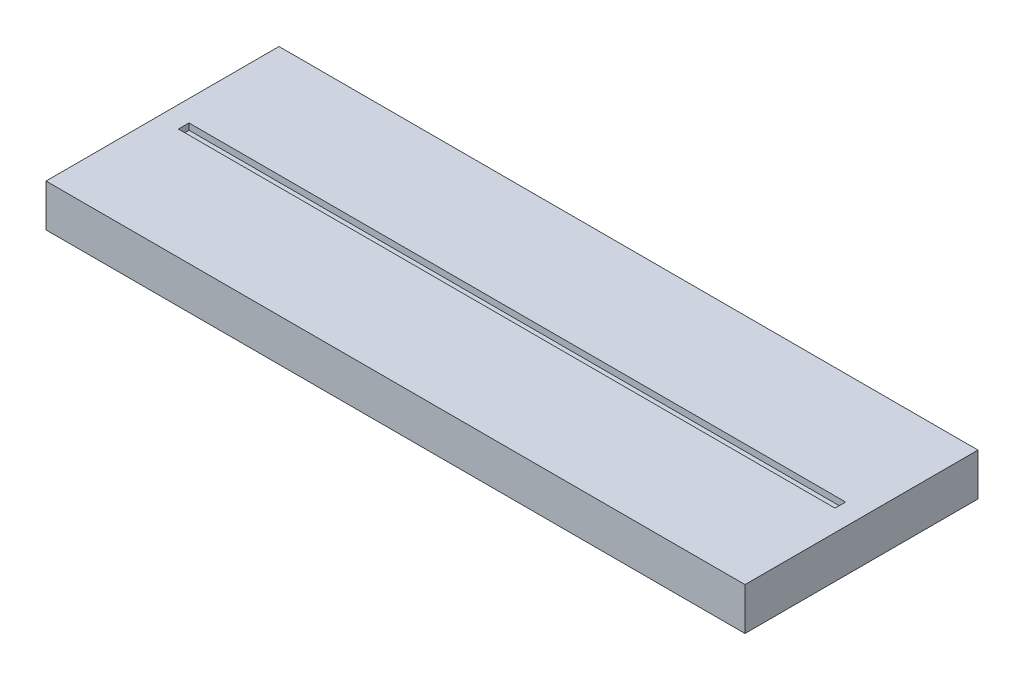
SolidWorks part; units mm, degrees
ref_plane "Front Plane" through (0, 0, 0) normal (0, 0, 1) x (1, 0, 0)
ref_plane "Top Plane" through (0, 0, 0) normal (0, 1, 0) x (1, 0, 0)
ref_plane "Right Plane" through (0, 0, 0) normal (1, 0, 0) x (0, 0, -1)
other "Configuration Table"
sketch "Sketch1" plane through (0, 0, 0) normal (0, 1, 0) x (1, 0, 0)
  line L1 (-82.5, -27.5) -> (82.5, -27.5)
  line L2 (-82.5, -27.5) -> (-82.5, 27.5)
  line L3 (-82.5, 27.5) -> (82.5, 27.5)
  line L4 (82.5, -27.5) -> (82.5, 27.5)
  line L5 (-82.5, -27.5) -> (82.5, 27.5) construction
  line L6 (-82.5, 27.5) -> (82.5, -27.5) construction
  point P6 (0, 0)
  dimension "D1" = 165
  dimension "D2" = 55
extrude "Body" add sketch "Sketch1" along normal blind 10
sketch "Sketch2" plane through (0, 0, 0) normal (0, 1, 0) x (1, 0, 0)
  line L0 (-77.5, -1.25) -> (77.5, -1.25)
  line L1 (77.5, -1.25) -> (77.5, 1.25)
  line L2 (77.5, 1.25) -> (-77.5, 1.25)
  line L3 (-77.5, 1.25) -> (-77.5, -1.25)
extrude "Centre_Channel" cut sketch "Sketch2" against normal blind 1.5 from offset 10
equation "\"Jar_OD\"= 90  'ASSUMED - Part G fallback - jar outer diameter"
equation "\"Jar_H\"= 120  'ASSUMED - Part G fallback - jar height"
equation "\"Pump_L\"= 45  'ASSUMED - Part G fallback"
equation "\"Pump_W\"= 24  'ASSUMED - Part G fallback"
equation "\"Pump_H\"= 33  'ASSUMED - Part G fallback"
equation "\"Pump_Outlet_OD\"= 7.5  'ASSUMED - Part G fallback"
equation "\"Tube_OD\"= 8  'ASSUMED - Part G fallback"
equation "\"Tube_ID\"= 6  'ASSUMED - Part G fallback"
equation "\"TDS_Body_Dia\"= 12  'ASSUMED - Part G fallback"
equation "\"TDS_Wet_Len\"= 45  'ASSUMED - Part G fallback - length in water"
equation "\"DS_Tube_Dia\"= 6  'ASSUMED - Part G fallback"
equation "\"DS_Tube_Len\"= 50  'ASSUMED - Part G fallback"
equation "\"ORP_Body_Dia\"= 12  'ASSUMED - Part G fallback"
equation "\"ORP_Body_Len\"= 150  'ASSUMED - Part G fallback"
equation "\"ORP_Cap_Dia\"= 16  'ASSUMED - Part G fallback"
equation "\"Turb_W\"= 33  'ASSUMED - Part G fallback - head width"
equation "\"Turb_D\"= 28  'ASSUMED - Part G fallback - head depth"
equation "\"Turb_H\"= 30  'ASSUMED - Part G fallback - head height"
equation "\"Turb_Slot_W\"= 10  'ASSUMED - Part G fallback - slot width"
equation "\"Flow_L\"= 62  'ASSUMED - Part G fallback YF-S201"
equation "\"Flow_W\"= 36  'ASSUMED - Part G fallback"
equation "\"Flow_H\"= 35  'ASSUMED - Part G fallback"
equation "\"Thread_G12_OD\"= 20.955  'ASSUMED - Part G fallback thread G1/2 (major diameter)"
equation "\"Valve_L\"= 75  'ASSUMED - Part G fallback"
equation "\"Valve_W\"= 45  'ASSUMED - Part G fallback"
equation "\"Valve_H\"= 60  'ASSUMED - Part G fallback"
equation "\"Tee_L\"= 40  'ASSUMED - Part G fallback - overall length"
equation "\"Tee_Branch_L\"= 25  'ASSUMED - Part G fallback"
equation "\"Tee_OD\"= 12  'ASSUMED - Part G fallback"
equation "\"LED_Board_L\"= 20  'ASSUMED - Part G fallback"
equation "\"LED_Board_W\"= 20  'ASSUMED - Part G fallback - LED at centre"
equation "\"GUVA_L\"= 20  'ASSUMED - Part G fallback"
equation "\"GUVA_W\"= 12  'ASSUMED - Part G fallback - sensor at centre"
equation "\"Reed_L\"= 27  'ASSUMED - Part G fallback MC-38 half"
equation "\"Reed_W\"= 14  'ASSUMED - Part G fallback"
equation "\"Reed_H\"= 8  'ASSUMED - Part G fallback"
equation "\"ESP_L\"= 51  'ASSUMED - Part G fallback"
equation "\"ESP_W\"= 28  'ASSUMED - Part G fallback"
equation "\"TFT_L\"= 58  'ASSUMED - Part G fallback - board"
equation "\"TFT_W\"= 35  'ASSUMED - Part G fallback - board"
equation "\"TFT_Win_L\"= 35  'ASSUMED - Part G fallback - visible window"
equation "\"TFT_Win_W\"= 28  'ASSUMED - Part G fallback - visible window"
equation "\"Relay_L\"= 50  'ASSUMED - Part G fallback"
equation "\"Relay_W\"= 26  'ASSUMED - Part G fallback"
equation "\"Relay_H\"= 19  'ASSUMED - Part G fallback"
equation "\"Mosfet_L\"= 34  'ASSUMED - Part G fallback"
equation "\"Mosfet_W\"= 17  'ASSUMED - Part G fallback"
equation "\"Mosfet_H\"= 12  'ASSUMED - Part G fallback"
equation "\"TDS_Board_L\"= 42  'ASSUMED - Part G fallback"
equation "\"TDS_Board_W\"= 32  'ASSUMED - Part G fallback"
equation "\"Turb_Board_L\"= 38  'ASSUMED - Part G fallback"
equation "\"Turb_Board_W\"= 28  'ASSUMED - Part G fallback"
equation "\"BNC_Thread_Dia\"= 9.5  'ASSUMED - Part G fallback"
equation "\"Plate_L\"= 420  'ASSUMED - Part G fallback"
equation "\"Plate_W\"= 297  'ASSUMED - Part G fallback"
equation "\"Plate_T\"= 6  'ASSUMED - Part G fallback"
equation "\"Booster_L\"= 150  'ASSUMED - Part G fallback - booster pump"
equation "\"Booster_W\"= 95  'ASSUMED - Part G fallback"
equation "\"Booster_H\"= 100  'ASSUMED - Part G fallback"
equation "\"PTube_OD\"= 6.35  'ASSUMED - Part G fallback - product tube 1/4 inch"
equation "\"Qz_Out\"= 12  'ASSUMED - Part G fallback - quartz channel outside square"
equation "\"Qz_Path\"= 10  'ASSUMED - Part G fallback - quartz channel inside light path"
equation "\"Qz_L\"= 40  'ASSUMED - Part G fallback - quartz channel length"
equation "\"LED860_Dia\"= 5  'ASSUMED - Part G fallback - 860 nm LED"
equation "\"BPW_L\"= 5.4  'ASSUMED - Part G fallback - BPW34"
equation "\"BPW_W\"= 4.3  'ASSUMED - Part G fallback - BPW34"
equation "\"Cart_Dia\"= 50  'ASSUMED - Part G fallback - sediment and pre-carbon cartridges"
equation "\"Cart_L\"= 255  'ASSUMED - Part G fallback"
equation "\"UF_Dia\"= 50  'ASSUMED - Part G fallback - UF cartridge"
equation "\"UF_L\"= 260  'ASSUMED - Part G fallback"
equation "\"RO_Dia\"= 62  'ASSUMED - Part G fallback - RO membrane housing"
equation "\"RO_L\"= 300  'ASSUMED - Part G fallback"
equation "\"UVC_Dia\"= 40  'ASSUMED - Part G fallback - UV-C chamber"
equation "\"UVC_L\"= 300  'ASSUMED - Part G fallback"
equation "\"Tank_W\"= 260  'ASSUMED - Part G fallback - storage tank"
equation "\"Tank_D\"= 160  'ASSUMED - Part G fallback"
equation "\"Tank_H\"= 300  'ASSUMED - Part G fallback"
equation "\"Cab_W\"= 400  'ASSUMED - Part G fallback - purifier cabinet"
equation "\"Cab_D\"= 270  'ASSUMED - Part G fallback"
equation "\"Cab_H\"= 560  'ASSUMED - Part G fallback"
equation "\"ORP_Board_L\"= 40  'ASSUMED - Part G fallback - ORP buffer board"
equation "\"ORP_Board_W\"= 30  'ASSUMED - Part G fallback"
equation "\"Opt_Board_L\"= 50  'ASSUMED - Part G fallback - optical front-end board"
equation "\"Opt_Board_W\"= 40  'ASSUMED - Part G fallback"
equation "\"Buck_L\"= 43  'ASSUMED - Part G fallback - 12 V to 5 V buck module"
equation "\"Buck_W\"= 21  'ASSUMED - Part G fallback"
equation "\"Buck_H\"= 14  'ASSUMED - Part G fallback"
equation "\"BB_L\"= 165  'ASSUMED - Part G fallback - breadboard (As_Built_R3 only)"
equation "\"BB_W\"= 55  'ASSUMED - Part G fallback"
equation "\"BB_H\"= 10  'ASSUMED - Part G fallback"
equation "\"Cuv_W\"= 12.5  'ASSUMED - old R3 cuvette (station suppressed in SS4)"
equation "\"Cuv_D\"= 12.5  'ASSUMED - old R3 cuvette (station suppressed in SS4)"
equation "\"Cuv_H\"= 45  'ASSUMED - old R3 cuvette (station suppressed in SS4)"
equation "\"Probe_Clr\"= 0.3  'DESIGN VALUE - Part C rule 3 - printed probe hole = diameter + 0.3"
equation "\"Label_H\"= 0.6  'DESIGN VALUE - Part D - raised label height"
equation "\"D1@Sketch1\" = \"BB_L\""
equation "\"D2@Sketch1\" = \"BB_W\""
equation "\"D1@Body\" = \"BB_H\""
